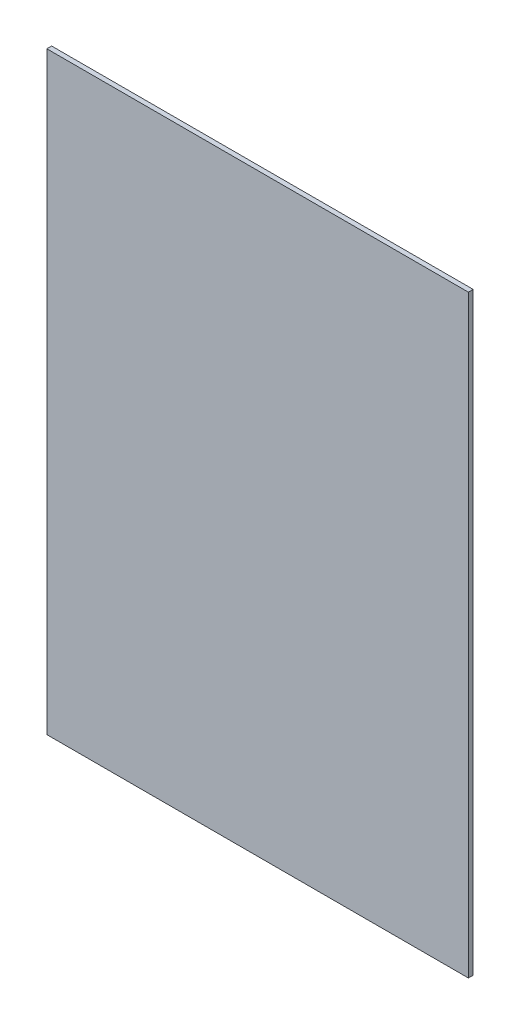
SolidWorks part; units mm, degrees
ref_plane "Plan de face" through (0, 0, 0) normal (0, 0, 1) x (1, 0, 0)
ref_plane "Plan de dessus" through (0, 0, 0) normal (0, 1, 0) x (1, 0, 0)
ref_plane "Plan de droite" through (0, 0, 0) normal (1, 0, 0) x (0, 0, -1)
sketch "Esquisse1" plane through (0, 0, 0) normal (0, 0, 1) x (1, 0, 0)
  line L1 (-220, -310) -> (220, -310)
  line L2 (-220, -310) -> (-220, 310)
  line L3 (-220, 310) -> (220, 310)
  line L4 (220, -310) -> (220, 310)
  line L5 (-220, -310) -> (220, 310) construction
  line L6 (-220, 310) -> (220, -310) construction
  point P0 (0, 0)
  dimension "D1" = 440
  dimension "D2" = 620
extrude "Boss.-Extru.1" add sketch "Esquisse1" along normal blind 5
